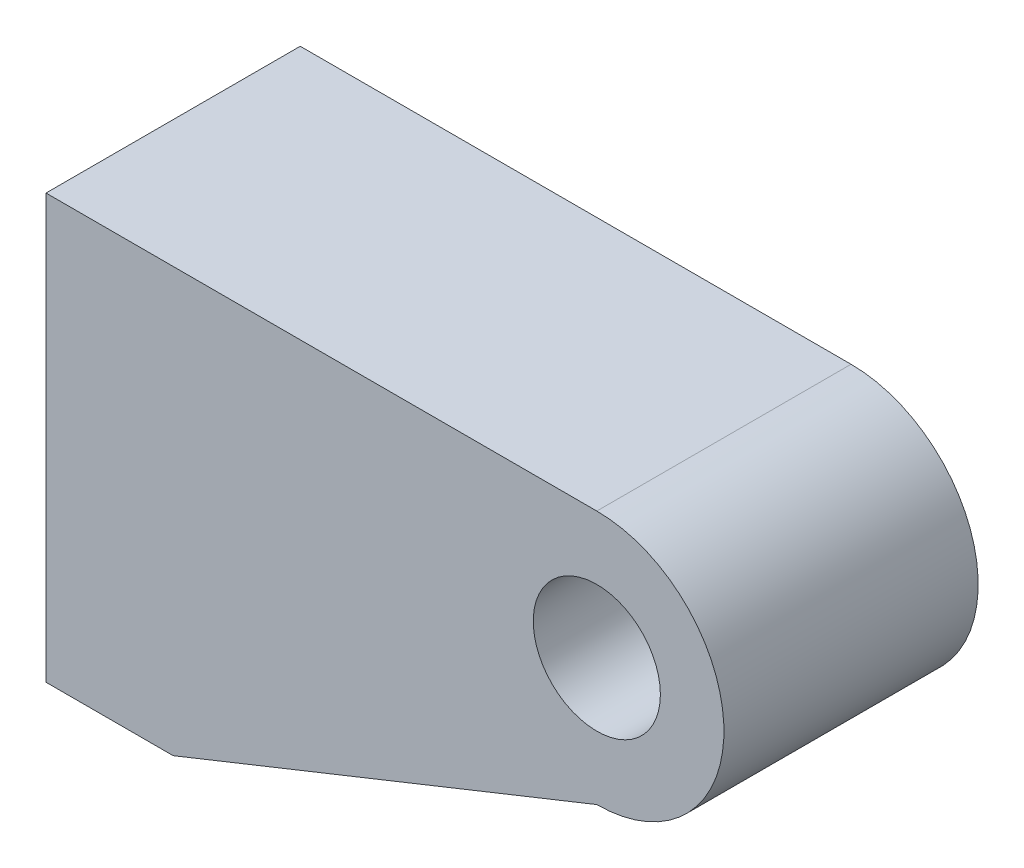
SolidWorks part; units mm, degrees
ref_plane "Front Plane" through (0, 0, 0) normal (0, 0, 1) x (1, 0, 0)
ref_plane "Top Plane" through (0, 0, 0) normal (0, 1, 0) x (1, 0, 0)
ref_plane "Right Plane" through (0, 0, 0) normal (1, 0, 0) x (0, 0, -1)
sketch "Sketch1" plane through (0, 0, 0) normal (0, 0, 1) x (1, 0, 0)
  line L0 (0, 0) -> (13, 0)
  line L1 (0, 0) -> (0, -10)
  line L2 (0, -10) -> (3, -10)
  line L3 (3, -10) -> (13, -6)
  arc A0 (13, 0) -> (13, -6) centre (13, -3) cw
  circle A1 centre (13, -3) radius 1.5
  dimension "D4" = 3
  dimension "D5" = 13
  dimension "D1" = 10
  dimension "D2" = 6
  dimension "D3" = 3
extrude "Boss-Extrude1" add sketch "Sketch1" along normal blind 6
